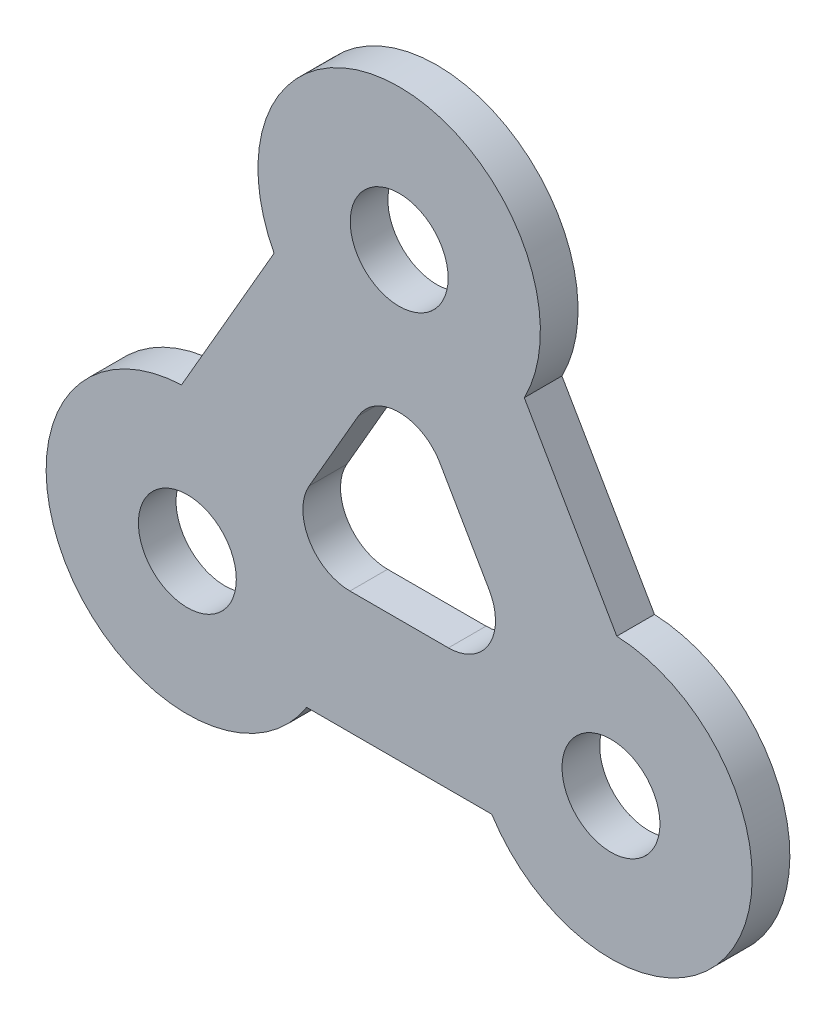
SolidWorks part; units mm, degrees
ref_plane "前视基准面" through (0, 0, 0) normal (0, 0, 1) x (1, 0, 0)
ref_plane "上视基准面" through (0, 0, 0) normal (0, 1, 0) x (1, 0, 0)
ref_plane "右视基准面" through (0, 0, 0) normal (1, 0, 0) x (0, 0, -1)
sketch "草图1" plane through (0, 0, 0) normal (0, 0, 1) x (1, 0, 0)
  line L0 (-18.4946, 4.743) -> (-23.4095, -3.7697)
  line L1 (-18.4946, 4.743) -> (-13.5798, 13.2557)
  line L2 (-0.2914, -26.7859) -> (9.5382, -26.7859)
  line L3 (-0.2914, -26.7859) -> (-10.1211, -26.7859)
  line L4 (17.9118, 4.743) -> (12.9969, 13.2557)
  line L5 (17.9118, 4.743) -> (22.8266, -3.7697)
  line L6 (9.2682, -6.2859) -> (4.0387, 2.7719)
  line L7 (-4.6216, 2.7719) -> (-9.851, -6.2859)
  line L8 (4.938, -13.7859) -> (-5.5209, -13.7859)
  line L9 (-0.2914, 20.2141) -> (22.2086, -18.757) construction
  line L10 (-0.2914, 20.2141) -> (-22.7914, -18.757) construction
  line L11 (-22.7914, -18.757) -> (22.2086, -18.757) construction
  circle A0 centre (-0.2914, 20.2141) radius 5.2
  circle A1 centre (22.2086, -18.757) radius 5.2
  circle A2 centre (-22.7914, -18.757) radius 5.2
  circle A3 centre (-0.2914, 0.2719) radius 5 construction
  circle A4 centre (4.938, -8.7859) radius 5 construction
  circle A5 centre (-5.5209, -8.7859) radius 5 construction
  circle A6 centre (-0.2914, 20.2141) radius 15 construction
  circle A7 centre (22.2086, -18.757) radius 15 construction
  circle A8 centre (-22.7914, -18.757) radius 15 construction
  arc A9 (12.9969, 13.2557) -> (-13.5798, 13.2557) centre (-0.2914, 20.2141) ccw
  arc A10 (22.8266, -3.7697) -> (9.5382, -26.7859) centre (22.2086, -18.757) cw
  arc A11 (-10.1211, -26.7859) -> (-23.4095, -3.7697) centre (-22.7914, -18.757) cw
  arc A12 (-5.5209, -13.7859) -> (-9.851, -6.2859) centre (-5.5209, -8.7859) cw
  arc A13 (4.938, -13.7859) -> (9.2682, -6.2859) centre (4.938, -8.7859) ccw
  arc A14 (4.0387, 2.7719) -> (-4.6216, 2.7719) centre (-0.2914, 0.2719) ccw
  dimension "D1" = 45
  dimension "D2" = 10.4
extrude "凸台-拉伸1" add sketch "草图1" along normal blind 4
